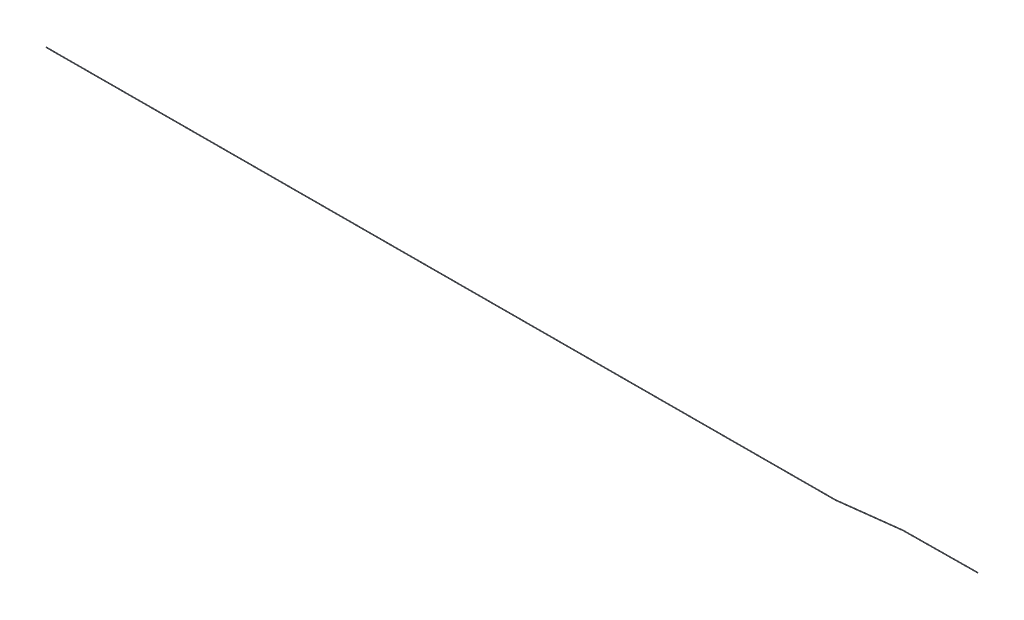
SolidWorks part; units mm, degrees
material "Nickel"
ref_plane "Front Plane" through (0, 0, 0) normal (0, 0, 1) x (1, 0, 0)
ref_plane "Top Plane" through (0, 0, 0) normal (0, 1, 0) x (1, 0, 0)
ref_plane "Right Plane" through (0, 0, 0) normal (1, 0, 0) x (0, 0, -1)
sketch3d "3DSketch1"
  line L0 (-389.0625, -1.1644, 3.3635) -> (275.8375, 0.816, 3.1636)
  line L1 (326.3546, 0.8536, -3.0653) -> (275.8375, 0.816, 3.1636)
  line L2 (326.3546, 0.8536, -3.0653) -> (389.0625, 1.1644, -3.3635)
sweep "Sweep2" add path "3DSketch1" circular profile diameter 0.45 parameters "D3"=0.45
